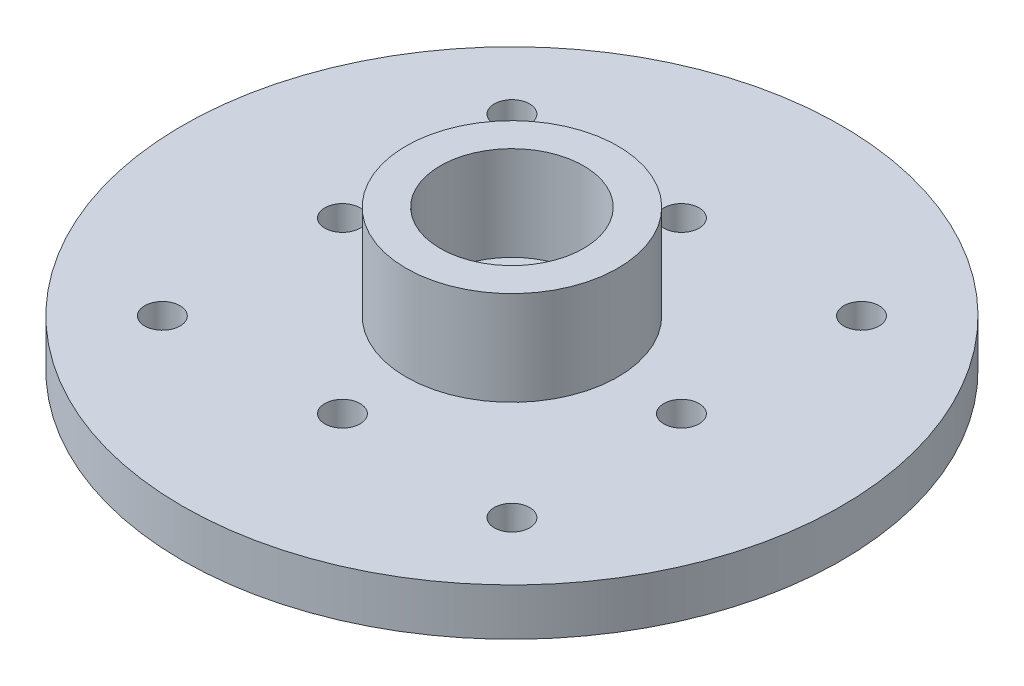
SolidWorks part; units mm, degrees
ref_plane "Plan de face" through (0, 0, 0) normal (0, 0, 1) x (1, 0, 0)
ref_plane "Plan de dessus" through (0, 0, 0) normal (0, 1, 0) x (1, 0, 0)
ref_plane "Plan de droite" through (0, 0, 0) normal (1, 0, 0) x (0, 0, -1)
sketch "Esquisse1" plane through (0, 0, 0) normal (0, 1, 0) x (1, 0, 0)
  circle A0 centre (0, 0) radius 14
  circle A1 centre (0, 7.2) radius 0.75
  circle A2 centre (7.4246, 7.4246) radius 0.75
  circle A3 centre (7.4246, -7.4246) radius 0.75
  circle A4 centre (7.2, 0) radius 0.75
  circle A5 centre (-7.4246, -7.4246) radius 0.75
  circle A6 centre (0, -7.2) radius 0.75
  circle A7 centre (-7.4246, 7.4246) radius 0.75
  circle A8 centre (-7.2, 0) radius 0.75
  point P22 (0, 0)
  dimension "D1" = 28
  dimension "D2" = 1.5
  dimension "D3" = 1.5
  dimension "D4" = 7.2
  dimension "D5" = 10.5
  dimension "D7" = 4
extrude "Boss.-Extru.1" add sketch "Esquisse1" along normal blind 2
sketch "Esquisse2" plane through (0, 2, 0) normal (0, 1, 0) x (1, 0, 0)
  circle A0 centre (0, 0) radius 4.5
  dimension "D1" = 9
extrude "Boss.-Extru.2" add sketch "Esquisse2" along normal blind 4
sketch "Esquisse3" plane through (0, 6, 0) normal (0, 1, 0) x (1, 0, 0)
  circle A0 centre (0, 0) radius 3.0436
extrude "Enlèv. mat.-Extru.1" cut sketch "Esquisse3" against normal blind 4
sketch "Esquisse4" plane through (0, 2, 0) normal (0, 1, 0) x (1, 0, 0)
  circle A0 centre (0, 0) radius 1.75
  dimension "D1" = 3.5
extrude "Enlèv. mat.-Extru.2" cut sketch "Esquisse4" against normal blind 4
sketch "Esquisse5" plane through (0, 0, 0) normal (0, -1, 0) x (-1, 0, 0)
  circle A0 centre (0, 0) radius 3.5
  dimension "D1" = 7
extrude "Enlèv. mat.-Extru.3" cut sketch "Esquisse5" against normal blind 1.4
